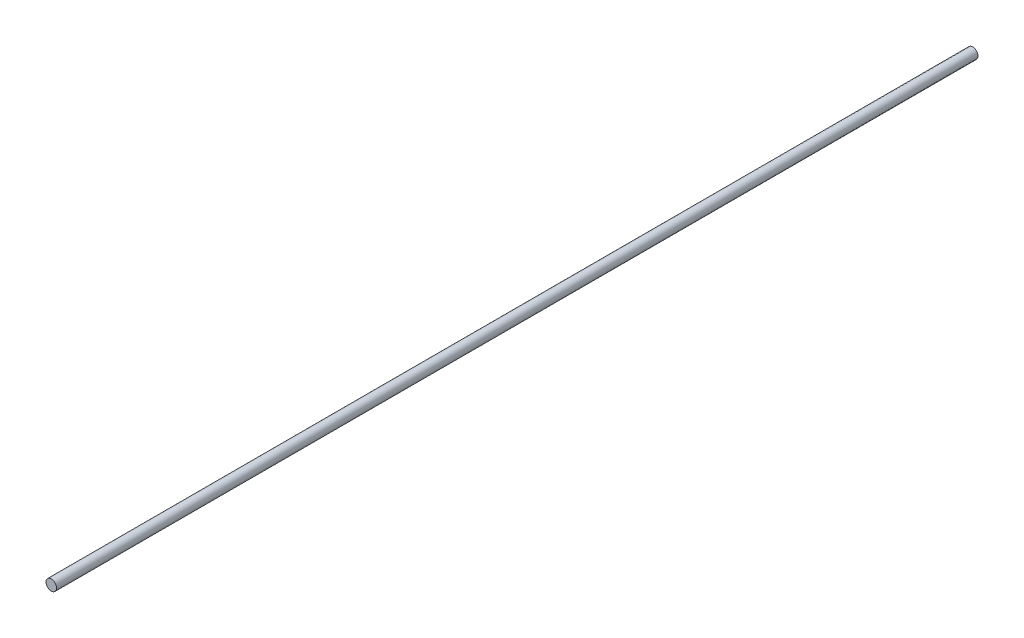
SolidWorks part; units mm, degrees
ref_plane "Plan de face" through (0, 0, 0) normal (0, 0, 1) x (1, 0, 0)
ref_plane "Plan de dessus" through (0, 0, 0) normal (0, 1, 0) x (1, 0, 0)
ref_plane "Plan de droite" through (0, 0, 0) normal (1, 0, 0) x (0, 0, -1)
sketch "Esquisse1" plane through (0, 0, 0) normal (0, 0, 1) x (1, 0, 0)
  circle A0 centre (0, 0) radius 4
  dimension "D1" = 8
extrude "Boss.-Extru.1" add sketch "Esquisse1" along normal blind 700
